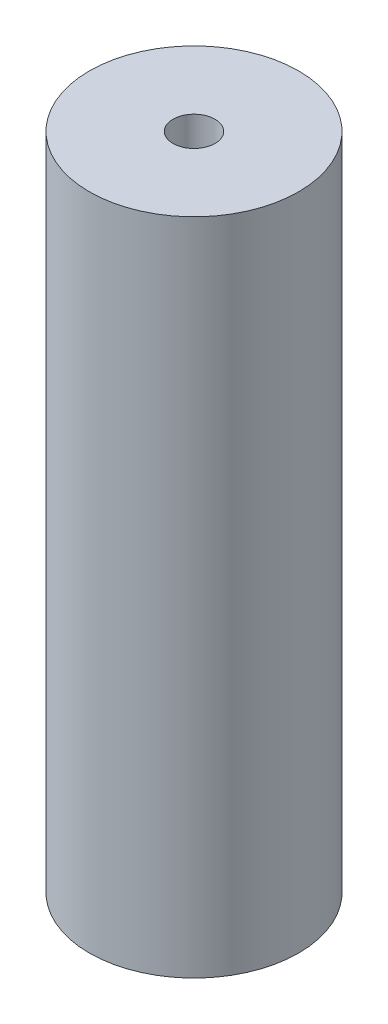
SolidWorks part; units mm, degrees
material "Delrin 2700 NC010, Low Viscosity Acetal Copolymer (SS)"
ref_plane "Front Plane" through (0, 0, 0) normal (0, 0, 1) x (1, 0, 0)
ref_plane "Top Plane" through (0, 0, 0) normal (0, 1, 0) x (1, 0, 0)
ref_plane "Right Plane" through (0, 0, 0) normal (1, 0, 0) x (0, 0, -1)
sketch "Sketch1" plane through (0, 0, 0) normal (0, 1, 0) x (1, 0, 0)
  circle A0 centre (0, 0) radius 12.7
  dimension "D1" = 25.4
extrude "Boss-Extrude1" add sketch "Sketch1" along normal blind 80
sketch "Sketch2" plane through (0, 0, 0) normal (0, -1, 0) x (1, 0, 0)
  point P0 (0, 0)
hole_wizard "Tap Drill for 1/4-20 Tap1" positions "Sketch2" profile "Sketch3" hole size "1/4-20" standard "ANSI Inch"
sketch "Sketch3" plane through (0, 0, 0) normal (1, 0, 0) x (0, 0, -1)
  line L0 (0, 0) -> (0, 9.1538)
  line L1 (0, 9.1538) -> (2.5527, 7.62)
  line L2 (2.5527, 7.62) -> (2.5527, 0)
  line L5 (2.5527, 0) -> (0, 0)
  line L10 (0, 9.1538) -> (-2.5527, 7.62) construction
  line L11 (0, -6.35) -> (0, 107.95) construction
  dimension "Hole Dia." = 5.1054
  dimension "Hole Depth" = 7.62
  dimension "Drill Angle" = 118
sketch "Sketch4" plane through (0, 80, 0) normal (0, 1, 0) x (1, 0, 0)
  point P0 (0, 0)
hole_wizard "Tap Drill for 1/4-20 Tap2" positions "Sketch4" profile "Sketch5" hole size "1/4-20" standard "ANSI Inch"
sketch "Sketch5" plane through (0, 80, 0) normal (1, 0, 0) x (0, 0, 1)
  line L0 (0, 0) -> (0, 9.1538)
  line L1 (0, 9.1538) -> (2.5527, 7.62)
  line L2 (2.5527, 7.62) -> (2.5527, 0)
  line L5 (2.5527, 0) -> (0, 0)
  line L10 (0, 9.1538) -> (-2.5527, 7.62) construction
  line L11 (0, -6.35) -> (0, 107.95) construction
  dimension "Hole Dia." = 5.1054
  dimension "Hole Depth" = 7.62
  dimension "Drill Angle" = 118
